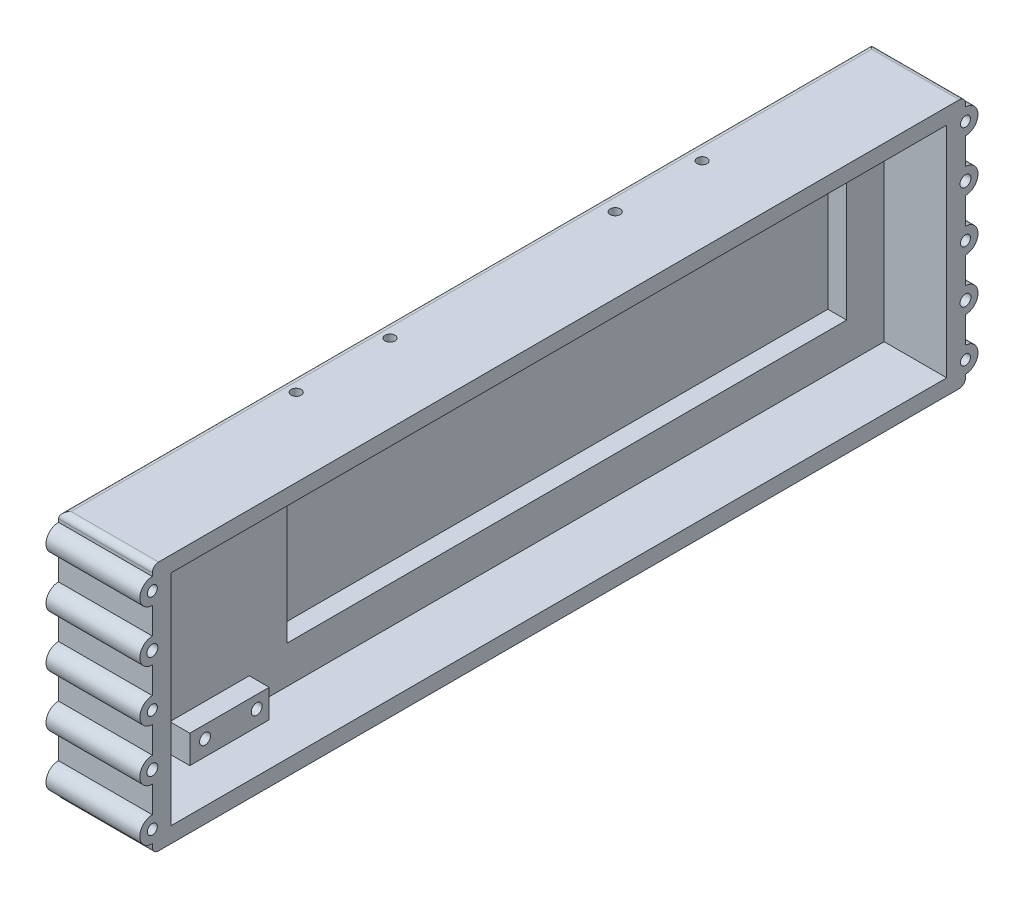
SolidWorks part; units mm, degrees
ref_plane "前视" through (0, 0, 0) normal (0, 0, 1) x (1, 0, 0)
ref_plane "上视" through (0, 0, 0) normal (0, 1, 0) x (1, 0, 0)
ref_plane "右视" through (0, 0, 0) normal (1, 0, 0) x (0, 0, -1)
sketch "草图1" plane through (0, 0, 0) normal (1, 0, 0) x (0, 0, -1)
  line L0 (-63, 18.5) -> (63, 18.5)
  line L1 (-62, 17.5) -> (62, 17.5)
  line L2 (-62, 17.5) -> (-62, -17.5)
  line L3 (-62, -17.5) -> (62, -17.5)
  line L4 (62, 17.5) -> (62, -17.5)
  line L5 (63, 18.5) -> (63, -18.5)
  line L6 (-63, -18.5) -> (63, -18.5)
  line L7 (-63, 18.5) -> (-63, -18.5)
  dimension "D1" = 124
  dimension "D2" = 35
  dimension "D3" = 17.5
  dimension "D4" = 62
  dimension "D5" = 1
extrude "凸台-拉伸1" add sketch "草图1" along normal blind 10
sketch "草图2" plane through (0, 0, 0) normal (-1, 0, 0) x (0, 0, 1)
  line L4 (63, -18.5) -> (63, 18.5)
  line L5 (63, 18.5) -> (-63, 18.5)
  line L6 (-63, 18.5) -> (-63, -18.5)
  line L7 (-63, -18.5) -> (63, -18.5)
  line L8 (63, -18.5) -> (63, 18.5)
  line L9 (63, 18.5) -> (-63, 18.5)
  line L10 (-63, 18.5) -> (-63, -18.5)
  line L11 (-63, -18.5) -> (63, -18.5)
  dimension "D1" = 0
extrude "凸台-拉伸2" add sketch "草图2" against normal blind 1
sketch "草图3" plane through (0, 0, -63) normal (0, 0, -1) x (-1, 0, 0)
  line L4 (0, -18.5) -> (0, 18.5)
  line L5 (0, 18.5) -> (-10, 18.5)
  line L6 (-10, 18.5) -> (-10, -18.5)
  line L7 (-10, -18.5) -> (0, -18.5)
  line L8 (0, -18.5) -> (0, 18.5)
  line L9 (0, 18.5) -> (-10, 18.5)
  line L10 (-10, 18.5) -> (-10, -18.5)
  line L11 (-10, -18.5) -> (0, -18.5)
  dimension "D1" = 0
extrude "凸台-拉伸3" add sketch "草图3" along normal blind 2
sketch "草图4" plane through (0, 0, 63) normal (0, 0, 1) x (1, 0, 0)
  line L4 (0, 18.5) -> (0, -18.5)
  line L5 (0, -18.5) -> (10, -18.5)
  line L6 (10, -18.5) -> (10, 18.5)
  line L7 (10, 18.5) -> (0, 18.5)
  line L8 (0, 18.5) -> (0, -18.5)
  line L9 (0, -18.5) -> (10, -18.5)
  line L10 (10, -18.5) -> (10, 18.5)
  line L11 (10, 18.5) -> (0, 18.5)
  dimension "D1" = 0
extrude "凸台-拉伸4" add sketch "草图4" along normal blind 2
sketch "草图5" plane through (1, 0, 0) normal (1, 0, 0) x (0, 0, -1)
  line L0 (62, -17.5) -> (-62, -17.5) construction
  line L1 (-62, 17.5) -> (-39.5, 17.5)
  line L2 (-62, 17.5) -> (-62, -17.5)
  line L3 (-62, -17.5) -> (-39.5, -17.5)
  line L4 (-39.5, 17.5) -> (-39.5, -17.5)
  dimension "D1" = 22.5
extrude "凸台-拉伸5" add sketch "草图5" along normal blind 2.19
sketch "草图6" plane through (3.19, 0, 0) normal (1, 0, 0) x (0, 0, -1)
  line L4 (-62, 17.5) -> (-62, -17.5)
  line L5 (-62, -17.5) -> (-39.5, -17.5)
  line L6 (-39.5, -17.5) -> (-39.5, 17.5)
  line L7 (-39.5, 17.5) -> (-62, 17.5)
  line L8 (-62, 17.5) -> (-62, -17.5)
  line L9 (-62, -17.5) -> (-39.5, -17.5)
  line L10 (-39.5, -17.5) -> (-39.5, 17.5) construction
  line L11 (-39.5, 17.5) -> (-62, 17.5)
  line L13 (-60.2, 15.7) -> (-41.3, 15.7)
  line L14 (-60.2, 15.7) -> (-60.2, 13)
  line L15 (-60.2, 13) -> (-41.3, 13)
  line L16 (-60.2, 15.7) -> (-60.2, -15.7)
  line L17 (-60.2, -15.7) -> (-41.3, -15.7)
  line L18 (-41.3, -15.7) -> (-41.3, 15.7)
  line L19 (-41.3, 15.7) -> (-60.2, 15.7)
  line L20 (-60.2, 15.7) -> (-60.2, -15.7)
  line L21 (-60.2, -15.7) -> (-41.3, -15.7)
  line L22 (-41.3, -15.7) -> (-41.3, 15.7)
  line L23 (-41.3, 15.7) -> (-60.2, 15.7)
  line L24 (-41.3, 15.7) -> (-41.3, 13)
  line L25 (-41.3, -15.7) -> (-60.2, -15.7)
  line L26 (-41.3, -15.7) -> (-41.3, -13)
  line L27 (-41.3, -13) -> (-60.2, -13)
  line L28 (-60.2, -15.7) -> (-60.2, -13)
  dimension "D3" = 4.5
  dimension "D5" = 4.5
  dimension "D1" = 0
  dimension "D2" = 1.8
extrude "切除-拉伸2" cut sketch "草图6" against normal blind 7 contours L21 L28 L27 L22 L15 L14 L23 L20
sketch "草图7" plane through (3.19, 0, 0) normal (1, 0, 0) x (0, 0, -1)
  line L0 (-39.5, -17.5) -> (-39.5, 17.5) construction
  line L1 (-41.3, 13) -> (-39.5, 13)
  line L2 (-41.3, 13) -> (-41.3, -13)
  line L3 (-41.3, -13) -> (-39.5, -13)
  line L4 (-39.5, 13) -> (-39.5, -13)
extrude "切除-拉伸3" cut sketch "草图7" against normal blind 4
sketch "草图8" plane through (3.19, 0, 0) normal (1, 0, 0) x (0, 0, -1)
  line L0 (-39.5, -13) -> (-60.2, -13) construction
  line L1 (-39.5, -17.5) -> (-39.5, -13) construction
  line L2 (-39.5, -13) -> (-60.2, -13) construction
  circle A0 centre (-56.26, -15) radius 1
  circle A1 centre (-41.5, -15) radius 1
  circle A2 centre (-49.76, -15) radius 1
  dimension "D1" = 2
  dimension "D2" = 2
  dimension "D3" = 2
  dimension "D4" = 2
  dimension "D5" = 2
  dimension "D6" = 14.76
  dimension "D7" = 2
  dimension "D8" = 2
  dimension "D9" = 8.26
hole_wizard "M2.2x0.45 螺纹孔2" positions "3D草图1" profile "草图9" tap size "M2.2x0.45" standard "GB"
sketch3d "3D草图1"
  point P0 (3.19, -15, 41.5)
  point P6 (3.19, -15, 49.76)
sketch "草图9" plane through (3.19, -15, 41.5) normal (0, 1, 0) x (0, 0, -1)
  line L0 (0, 0) -> (0, 6.2758)
  line L1 (0, 6.2758) -> (0.875, 5.75)
  line L2 (0.875, 5.75) -> (0.875, 0)
  line L5 (0.875, 0) -> (0, 0)
  line L10 (0, 6.2758) -> (-0.875, 5.75) construction
  line L11 (0, -6.35) -> (0, 107.95) construction
  dimension "螺纹孔钻头直径" = 1.75
  dimension "螺纹孔钻头深度" = 5.75
  dimension "导头角度" = 118
cosmetic thread "孔螺蚊线2" parameters "D1"=3.19, "D2"=2.2
cosmetic thread "孔螺蚊线5" parameters "D1"=3.19, "D2"=2.2
mirror "镜向1" about plane through (0, 0, 0) normal (0, 1, 0) of "M2.2x0.45 螺纹孔2"
sketch "草图10" plane through (0, 0, 0) normal (-1, 0, 0) x (0, 0, 1)
  line L0 (-65, -18.5) -> (-65, 18.5) construction
  circle A0 centre (-65, -16.5) radius 2
  dimension "D1" = 4
extrude "凸台-拉伸6" add sketch "草图10" against normal up to surface (10 mm away) up to face at (10, 0, 0)
pattern_linear "阵列(线性)1" count 5 spacing 8.25 along (0, 1, 0) of "凸台-拉伸6"
mirror "镜向2" about plane through (0, 0, 0) normal (0, 0, 1) of "阵列(线性)1", "凸台-拉伸6"
sketch "草图11" plane through (10, 0, 0) normal (1, 0, 0) x (0, 0, -1)
  circle A0 centre (-65, 8.25) radius 1
  circle A1 centre (-65, -8.25) radius 1
  dimension "D1" = 2
  dimension "D2" = 2
hole_wizard "M2.2x0.45 螺纹孔3" positions "3D草图2" profile "草图12" tap size "M2.2x0.45" standard "GB"
sketch3d "3D草图2"
  point P0 (10, 8.25, 65)
  point P3 (10, -8.25, 65)
sketch "草图12" plane through (10, 8.25, 65) normal (0, 1, 0) x (0, 0, -1)
  line L0 (0, 0) -> (0, 6.2758)
  line L1 (0, 6.2758) -> (0.875, 5.75)
  line L2 (0.875, 5.75) -> (0.875, 0)
  line L5 (0.875, 0) -> (0, 0)
  line L10 (0, 6.2758) -> (-0.875, 5.75) construction
  line L11 (0, -6.35) -> (0, 107.95) construction
  dimension "螺纹孔钻头直径" = 1.75
  dimension "螺纹孔钻头深度" = 5.75
  dimension "导头角度" = 118
cosmetic thread "孔螺蚊线3" parameters "D1"=4.4, "D2"=2.2
cosmetic thread "孔螺蚊线4" parameters "D1"=4.4, "D2"=2.2
sketch "草图13" plane through (0, 0, 0) normal (-1, 0, 0) x (0, 0, 1)
  circle A0 centre (65, -16.5) radius 0.8
  circle A1 centre (65, 0) radius 0.8
  circle A2 centre (65, 16.5) radius 0.8
  dimension "D1" = 1.6
  dimension "D2" = 1.6
  dimension "D3" = 1.6
extrude "切除-拉伸4" cut sketch "草图13" against normal through all
mirror "镜向3" about plane through (0, 0, 0) normal (0, 0, 1) of "切除-拉伸4", "M2.2x0.45 螺纹孔3"
sketch "草图14" plane through (0, 0, 0) normal (-1, 0, 0) x (0, 0, 1)
  line L10 (65, 10.25) -> (65, 14.5)
  line L11 (65, 18.5) -> (-65, 18.5)
  line L12 (-65, 14.5) -> (-65, 10.25)
  line L13 (-65, 6.25) -> (-65, 2)
  line L14 (-65, -2) -> (-65, -6.25)
  line L15 (-65, -10.25) -> (-65, -14.5)
  line L16 (-65, -18.5) -> (65, -18.5)
  line L17 (65, -14.5) -> (65, -10.25)
  line L18 (65, -6.25) -> (65, -2)
  line L19 (65, 2) -> (65, 6.25)
  line L20 (65, 10.25) -> (65, 14.5)
  line L21 (65, 18.5) -> (-65, 18.5)
  line L22 (-65, 14.5) -> (-65, 10.25)
  line L23 (-65, 6.25) -> (-65, 2)
  line L24 (-65, -2) -> (-65, -6.25)
  line L25 (-65, -10.25) -> (-65, -14.5)
  line L26 (-65, -18.5) -> (65, -18.5)
  line L27 (65, -14.5) -> (65, -10.25)
  line L28 (65, -6.25) -> (65, -2)
  line L29 (65, 2) -> (65, 6.25)
  circle A0 centre (65, -16.5) radius 0.8 construction
  circle A1 centre (65, -16.5) radius 0.8
  circle A2 centre (65, 0) radius 0.8 construction
  circle A3 centre (65, 0) radius 0.8
  circle A4 centre (65, 16.5) radius 0.8 construction
  circle A5 centre (65, 16.5) radius 0.8
  circle A6 centre (-65, 16.5) radius 0.8 construction
  circle A7 centre (-65, 16.5) radius 0.8
  circle A8 centre (-65, 0) radius 0.8 construction
  circle A9 centre (-65, 0) radius 0.8
  arc A10 (65, 14.5) -> (65, 18.5) centre (65, 16.5) ccw
  arc A11 (-65, 18.5) -> (-65, 14.5) centre (-65, 16.5) ccw
  arc A12 (-65, 10.25) -> (-65, 6.25) centre (-65, 8.25) ccw
  arc A13 (-65, 2) -> (-65, -2) centre (-65, 0) ccw
  arc A14 (-65, -6.25) -> (-65, -10.25) centre (-65, -8.25) ccw
  arc A15 (-65, -14.5) -> (-65, -18.5) centre (-65, -16.5) ccw
  arc A16 (65, -18.5) -> (65, -14.5) centre (65, -16.5) ccw
  arc A17 (65, -10.25) -> (65, -6.25) centre (65, -8.25) ccw
  arc A18 (65, -2) -> (65, 2) centre (65, 0) ccw
  arc A19 (65, 6.25) -> (65, 10.25) centre (65, 8.25) ccw
  arc A20 (65, 14.5) -> (65, 18.5) centre (65, 16.5) ccw
  arc A21 (-65, 18.5) -> (-65, 14.5) centre (-65, 16.5) ccw
  arc A22 (-65, 10.25) -> (-65, 6.25) centre (-65, 8.25) ccw
  arc A23 (-65, 2) -> (-65, -2) centre (-65, 0) ccw
  arc A24 (-65, -6.25) -> (-65, -10.25) centre (-65, -8.25) ccw
  arc A25 (-65, -14.5) -> (-65, -18.5) centre (-65, -16.5) ccw
  arc A26 (65, -18.5) -> (65, -14.5) centre (65, -16.5) ccw
  arc A27 (65, -10.25) -> (65, -6.25) centre (65, -8.25) ccw
  arc A28 (65, -2) -> (65, 2) centre (65, 0) ccw
  arc A29 (65, 6.25) -> (65, 10.25) centre (65, 8.25) ccw
  circle A30 centre (-65, -16.5) radius 0.8 construction
  circle A31 centre (-65, -16.5) radius 0.8
  circle A32 centre (49.76, -15) radius 0.875 construction
  circle A33 centre (49.76, -15) radius 0.875
  circle A34 centre (41.5, -15) radius 0.875 construction
  circle A35 centre (41.5, -15) radius 0.875
  circle A36 centre (41.5, 15) radius 0.875 construction
  circle A37 centre (41.5, 15) radius 0.875
  dimension "D1" = 0
extrude "凸台-拉伸7" add sketch "草图14" along normal blind 5
sketch "草图15" plane through (1, 0, 0) normal (1, 0, 0) x (0, 0, -1)
  line L1 (-39.5, -17.5) -> (62, -17.5)
  line L2 (-39.5, -17.5) -> (-39.5, 17.5)
  line L3 (-39.5, 17.5) -> (62, 17.5)
  line L4 (62, -17.5) -> (62, 17.5)
extrude "切除-拉伸5" cut sketch "草图15" against normal blind 1
sketch "草图16" plane through (3.19, 0, 0) normal (1, 0, 0) x (0, 0, -1)
  line L0 (-62, 17.5) -> (-62, -17.5) construction
  line L1 (-62, -17.5) -> (-39.5, -17.5) construction
  line L2 (-60.2, 13) -> (-60.2, -13) construction
  line L7 (-62, -5.5) -> (-52.2, -5.5)
  line L8 (-62, -5.5) -> (-62, -17.5)
  line L9 (-62, -17.5) -> (-52.2, -17.5)
  line L10 (-52.2, -5.5) -> (-52.2, -17.5)
  dimension "D1" = 12
  dimension "D2" = 8
sketch "草图17" plane through (0, 18.5, 0) normal (0, 1, 0) x (1, 0, 0)
  line L0 (-5, -65) -> (-5, 65) construction
  line L1 (-5, 65) -> (10, 65) construction
  line L2 (10, -45.3166) -> (10, -38.6834)
  line L3 (10, 65) -> (10, -65) construction
  arc A0 (10, -38.6834) -> (10, -45.3166) centre (5, -42) ccw
  dimension "D1" = 12
  dimension "D2" = 10
  dimension "D3" = 107
extrude "凸台-拉伸8" add sketch "草图17" along normal blind 4.5
sketch "草图18" plane through (0, 23, 0) normal (0, 1, 0) x (1, 0, 0)
  circle A0 centre (5, -42) radius 2.95
  dimension "D1" = 5.9
extrude "凸台-拉伸9" add sketch "草图18" along normal blind 3.5
sketch "草图19" plane through (0, 26.5, 0) normal (0, 1, 0) x (1, 0, 0)
  circle A0 centre (5, -42) radius 1.025
  dimension "D1" = 2.05
extrude "切除-拉伸7" cut sketch "草图19" against normal blind 0.65
sketch "草图20" plane through (0, 18.5, 0) normal (0, 1, 0) x (1, 0, 0)
  line L3 (10, 65) -> (-5, 65)
  line L4 (10, 65) -> (-5, 65)
  line L5 (10, -38.6834) -> (10, 65)
  line L6 (-5, 65) -> (-5, -65)
  line L7 (-5, 65) -> (-5, -65)
  line L10 (10, -38.6834) -> (10, 65)
  line L11 (-5, -65) -> (10, -65)
  line L12 (-5, -65) -> (10, -65)
  line L13 (10, -65) -> (10, -45.3166)
  line L14 (10, -65) -> (10, -45.3166)
  arc A1 (10, -38.6834) -> (10, -45.3166) centre (5, -42) ccw
  arc A2 (10, -38.6834) -> (10, -45.3166) centre (5, -42) ccw
  dimension "D1" = 0
extrude "凸台-拉伸10" add sketch "草图20" along normal blind 1.5
mirror "镜向6" about plane through (0, 0, 0) normal (0, 1, 0) of "凸台-拉伸10", "凸台-拉伸8", "凸台-拉伸9", "切除-拉伸7"
chamfer "倒角1" distance 1.5 angle 45 2 edges at (-1, -20, 42) (-1, 20, 42)
sketch "草图21" plane through (0, -20, 0) normal (0, -1, 0) x (1, 0, 0)
  line L0 (-2.5, 42) -> (-5, 42) construction
  line L1 (-5, -65) -> (-5, 65) construction
  circle A0 centre (-2.5, 29.5) radius 1
  circle A1 centre (-2.5, 14.5) radius 1
  arc A2 (10, 47.5902) -> (10, 36.4098) centre (5, 42) ccw construction
  circle A3 centre (-2.5, -10.5) radius 1
  circle A4 centre (-2.5, -45.5) radius 1
  dimension "D1" = 2
  dimension "D2" = 2
  dimension "D3" = 12.5
  dimension "D4" = 15
  dimension "D5" = 2.5
  dimension "D6" = 2.5
  dimension "D7" = 2
  dimension "D8" = 2.5
  dimension "D9" = 2
  dimension "D10" = 2.5
  dimension "D11" = 35
  dimension "D12" = 25
hole_wizard "M2 螺纹孔3" positions "3D草图3" profile "草图22" tap size "M2" standard "GB"
sketch3d "3D草图3"
  point P0 (-2.5, -20, 29.5)
  point P3 (-2.5, -20, 14.5)
  point P6 (-2.5, -20, -10.5)
  point P9 (-2.5, -20, -45.5)
sketch "草图22" plane through (-2.5, -20, 29.5) normal (1, 0, 0) x (0, 0, -1)
  line L0 (0, 0) -> (0, 5.6807)
  line L1 (0, 5.6807) -> (0.8, 5.2)
  line L2 (0.8, 5.2) -> (0.8, 0)
  line L5 (0.8, 0) -> (0, 0)
  line L10 (0, 5.6807) -> (-0.8, 5.2) construction
  line L11 (0, -6.35) -> (0, 107.95) construction
  dimension "螺纹孔钻头直径" = 1.6
  dimension "螺纹孔钻头深度" = 5.2
  dimension "导头角度" = 118
cosmetic thread "孔螺蚊线11" parameters "D1"=4, "D2"=2
cosmetic thread "孔螺蚊线12" parameters "D1"=4, "D2"=2
cosmetic thread "孔螺蚊线13" parameters "D1"=4, "D2"=2
cosmetic thread "孔螺蚊线14" parameters "D1"=4, "D2"=2
mirror "镜向7" about plane through (0, 0, 0) normal (0, 1, 0) of "M2 螺纹孔3"
fillet "圆角2" radius 0.5 2 edges at (5, 26.5, 44.95) (5, -26.5, 44.95)
sketch "草图23" plane through (3.19, 0, 0) normal (1, 0, 0) x (0, 0, -1)
  circle A0 centre (-49.76, 15) radius 1.4043
  dimension "D1" = 1.4043
extrude "凸台-拉伸11" add sketch "草图23" against normal blind 8
sketch "草图24" plane through (3.19, 0, 0) normal (1, 0, 0) x (0, 0, -1)
  line L0 (-41.5, 15) -> (-48.5, 15) construction
  circle A0 centre (-48.5, 15) radius 1
  dimension "D1" = 1
  dimension "D2" = 7
hole_wizard "M2.2x0.45 螺纹孔1" positions "3D草图4" profile "草图25" tap size "M2.2x0.45" standard "GB"
sketch3d "3D草图4"
  point P0 (3.19, 15, 48.5)
sketch "草图25" plane through (3.19, 15, 48.5) normal (0, 1, 0) x (0, 0, -1)
  line L0 (0, 0) -> (0, 6.2758)
  line L1 (0, 6.2758) -> (0.875, 5.75)
  line L2 (0.875, 5.75) -> (0.875, 0)
  line L5 (0.875, 0) -> (0, 0)
  line L10 (0, 6.2758) -> (-0.875, 5.75) construction
  line L11 (0, -6.35) -> (0, 107.95) construction
  dimension "螺纹孔钻头直径" = 1.75
  dimension "螺纹孔钻头深度" = 5.75
  dimension "导头角度" = 118
cosmetic thread "孔螺蚊线10" parameters "D1"=4.4, "D2"=2.2
extrude "切除-拉伸8" cut sketch "草图16" against normal blind 6
sketch "草图27" plane through (3.19, 0, 0) normal (1, 0, 0) x (0, 0, -1)
  line L0 (-52.2, -17.5) -> (-52.2, -13) construction
  line L1 (-60.2, 13) -> (-52.2, 13)
  line L2 (-60.2, 13) -> (-60.2, 16)
  line L3 (-60.2, 16) -> (-52.2, 16)
  line L4 (-52.2, 13) -> (-52.2, 16)
  dimension "D1" = 3
extrude "切除-拉伸9" cut sketch "草图27" against normal up to surface (3.19 mm away) up to face at (0, -1.1, 25.88)
sketch "草图28" plane through (0, -20, 0) normal (0, -1, 0) x (1, 0, 0)
  circle A0 centre (-2.5, -10.5) radius 1
  circle A1 centre (-2.5, -45.5) radius 2.0111
  dimension "D1" = 2
extrude "凸台-拉伸12" add sketch "草图28" against normal up to surface (40 mm away) up to face at (-2.5, 20, 30.3)
sketch "草图29" plane through (0, -20, 0) normal (0, -1, 0) x (1, 0, 0)
  line L0 (-5, -65) -> (-5, 65) construction
  line L1 (-2.1078, -35) -> (-5, -35) construction
  circle A0 centre (-2, -21) radius 1.1949
  circle A1 centre (-2.1078, -35) radius 1.1478
  circle A2 centre (-2.5, 14.5) radius 1 construction
  dimension "D1" = 3
  dimension "D2" = 14
  dimension "D3" = 35.5
hole_wizard "M2 螺纹孔5" positions "3D草图5" profile "草图30" tap size "M2" standard "GB"
sketch3d "3D草图5"
  point P0 (-2.1078, -20, -35)
  point P3 (-2, -20, -21)
sketch "草图30" plane through (-2.1078, -20, -35) normal (1, 0, 0) x (0, 0, -1)
  line L0 (0, 0) -> (0, 5.6807)
  line L1 (0, 5.6807) -> (0.8, 5.2)
  line L2 (0.8, 5.2) -> (0.8, 0)
  line L5 (0.8, 0) -> (0, 0)
  line L10 (0, 5.6807) -> (-0.8, 5.2) construction
  line L11 (0, -6.35) -> (0, 107.95) construction
  dimension "螺纹孔钻头直径" = 1.6
  dimension "螺纹孔钻头深度" = 5.2
  dimension "导头角度" = 118
cosmetic thread "孔螺蚊线15" parameters "D1"=4, "D2"=2
cosmetic thread "孔螺蚊线16" parameters "D1"=4, "D2"=2
mirror "镜向8" about plane through (0, 0, 0) normal (0, 1, 0) of "M2 螺纹孔5"
sketch "草图31" plane through (0, 0, 0) normal (1, 0, 0) x (0, 0, -1)
  line L0 (62, 17.5) -> (-39.5, 17.5) construction
  line L1 (-33.5, 11.5) -> (56, 11.5)
  line L2 (-33.5, 11.5) -> (-33.5, -11.5)
  line L3 (-33.5, -11.5) -> (56, -11.5)
  line L4 (56, 11.5) -> (56, -11.5)
  line L5 (-39.5, -17.5) -> (62, -17.5) construction
  line L6 (62, -17.5) -> (62, 17.5) construction
  line L7 (-39.5, -13) -> (-39.5, -17.5) construction
  dimension "D1" = 6
  dimension "D2" = 6
  dimension "D3" = 6
  dimension "D4" = 6
extrude "切除-拉伸10" cut sketch "草图31" against normal blind 3
fillet "圆角3" radius 1 6 edges at (2.5, 20, 65) (-5, -20, 0) (-5, 20, 0) (2.5, 20, -65) (2.5, -20, -65) (2.5, -20, 65)
fillet "圆角4" radius 0.5 2 edges at (5, 23, 44.95) (5, -23, 39.05)
sketch "草图32" plane through (3.19, 0, 0) normal (1, 0, 0) x (0, 0, -1)
  circle A0 centre (-48.5, 15) radius 0.875
extrude "切除-拉伸11" cut sketch "草图32" against normal blind 10
sketch "草图33" plane through (0, 25.85, 0) normal (0, 1, 0) x (1, 0, 0)
  circle A1 centre (5, -42) radius 1.025
  circle A2 centre (5, -42) radius 1.025
  dimension "D1" = 0
hole_wizard "M2.5 螺纹孔1" positions "3D草图7" profile "草图34" tap size "M2.5" standard "GB"
sketch3d "3D草图7"
  line L0 (5, 25.85, 42) -> (5, 26.5, 42) construction
  point P0 (5, 25.85, 42)
sketch "草图34" plane through (5, 25.85, 42) normal (1, 0, 0) x (0, 0, 1)
  line L0 (0, 0) -> (0, 4.9659)
  line L1 (0, 4.9659) -> (1.025, 4.35)
  line L2 (1.025, 4.35) -> (1.025, 0)
  line L5 (1.025, 0) -> (0, 0)
  line L10 (0, 4.9659) -> (-1.025, 4.35) construction
  line L11 (0, -6.35) -> (0, 107.95) construction
  dimension "螺纹孔钻头直径" = 2.05
  dimension "螺纹孔钻头深度" = 4.35
  dimension "导头角度" = 118
sketch "草图35" plane through (0, -25.85, 0) normal (0, -1, 0) x (1, 0, 0)
  circle A1 centre (5, 42) radius 1.025
  circle A2 centre (5, 42) radius 1.025
  dimension "D1" = 0
hole_wizard "M2.5 螺纹孔2" positions "3D草图8" profile "草图36" tap size "M2.5" standard "GB"
sketch3d "3D草图8"
  line L0 (5, -25.85, 42) -> (5, -26.5, 42) construction
  point P0 (5, -25.85, 42)
sketch "草图36" plane through (5, -25.85, 42) normal (1, 0, 0) x (0, 0, -1)
  line L0 (0, 0) -> (0, 4.9659)
  line L1 (0, 4.9659) -> (1.025, 4.35)
  line L2 (1.025, 4.35) -> (1.025, 0)
  line L5 (1.025, 0) -> (0, 0)
  line L10 (0, 4.9659) -> (-1.025, 4.35) construction
  line L11 (0, -6.35) -> (0, 107.95) construction
  dimension "螺纹孔钻头直径" = 2.05
  dimension "螺纹孔钻头深度" = 4.35
  dimension "导头角度" = 118
sketch "草图37" plane through (0, 0, 65) normal (0, 0, 1) x (1, 0, 0)
  line L0 (-3.5, -20) -> (-1.5, -20) construction
  line L1 (-2.5, 20) -> (13.3889, 20)
  line L2 (-2.5, 20) -> (-2.5, 28.8461)
  line L3 (-2.5, 28.8461) -> (13.3889, 28.8461)
  line L4 (13.3889, 20) -> (13.3889, 28.8461)
  line L5 (-2.5, -20) -> (10.4889, -20)
  line L6 (-2.5, -20) -> (-2.5, -27.121)
  line L7 (-2.5, -27.121) -> (10.4889, -27.121)
  line L8 (10.4889, -20) -> (10.4889, -27.121)
extrude "切除-拉伸12" cut sketch "草图37" against normal up to surface (130 mm away) up to face at (2.5, 12.375, -65)
